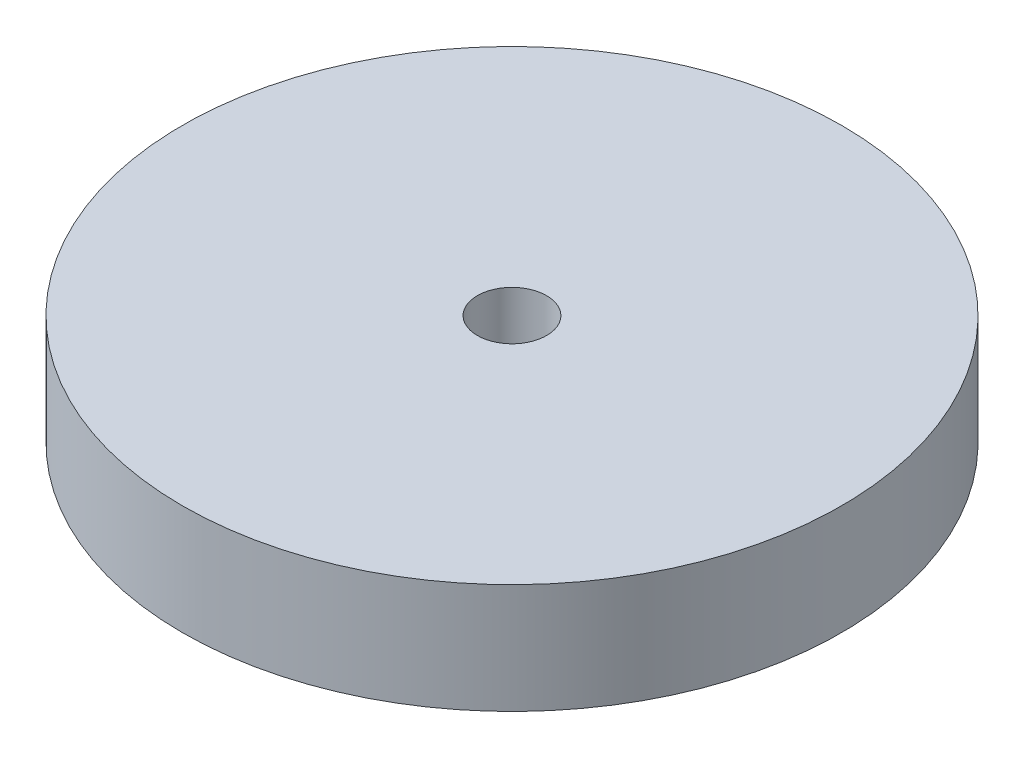
SolidWorks part; units mm, degrees
ref_plane "Plan de face" through (0, 0, 0) normal (0, 0, 1) x (1, 0, 0)
ref_plane "Plan de dessus" through (0, 0, 0) normal (0, 1, 0) x (1, 0, 0)
ref_plane "Plan de droite" through (0, 0, 0) normal (1, 0, 0) x (0, 0, -1)
sketch "Esquisse1" plane through (0, 0, 0) normal (0, 1, 0) x (1, 0, 0)
  circle A0 centre (0, 0) radius 30
  dimension "D1" = 60
extrude "Boss.-Extru.1" add sketch "Esquisse1" along normal blind 10
sketch "Esquisse2" plane through (0, 10, 0) normal (0, 1, 0) x (1, 0, 0)
  circle A0 centre (0, 0) radius 3.15
  dimension "D1" = 6.3
extrude "Enlèv. mat.-Extru.1" cut sketch "Esquisse2" against normal through all
